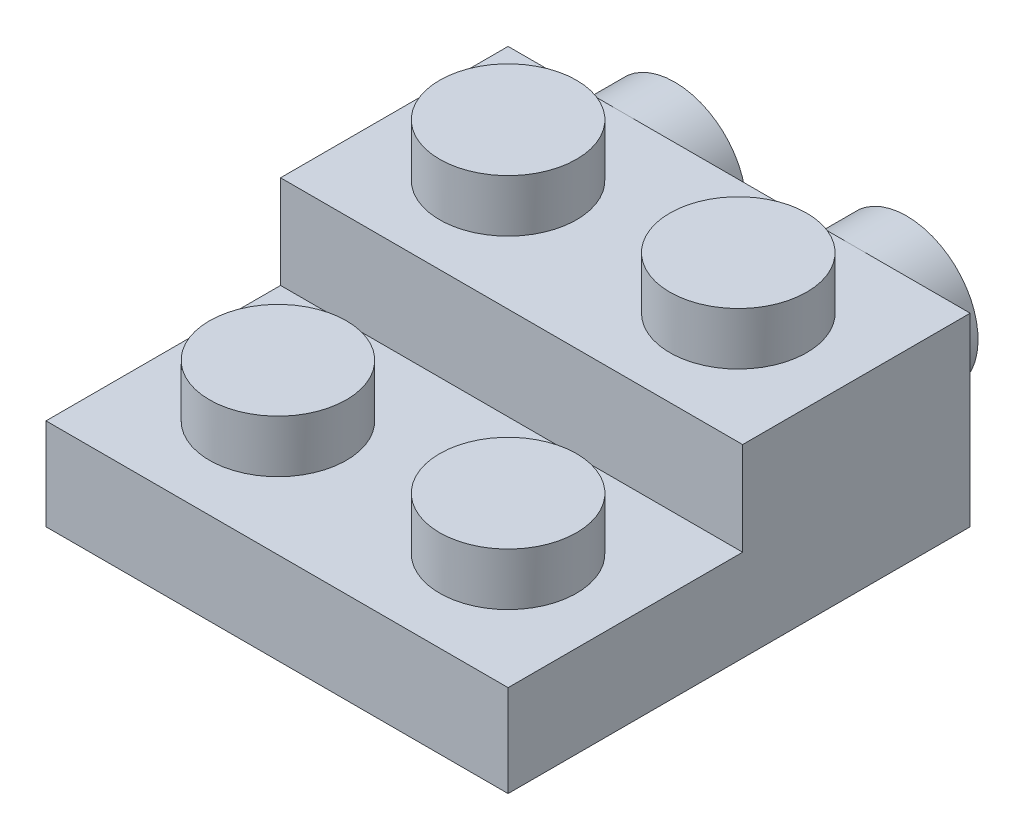
SolidWorks part; units mm, degrees
ref_plane "Front Plane" through (0, 0, 0) normal (0, 0, 1) x (1, 0, 0)
ref_plane "Top Plane" through (0, 0, 0) normal (0, 1, 0) x (1, 0, 0)
ref_plane "Right Plane" through (0, 0, 0) normal (1, 0, 0) x (0, 0, -1)
sketch "Sketch2" plane through (0, 0, 0) normal (1, 0, 0) x (0, 0, -1)
  line L0 (0, 0) -> (0, 6.35)
  line L1 (0, 6.35) -> (-7.81, 6.35)
  line L2 (-7.81, 6.35) -> (-7.81, 3.15)
  line L3 (-7.81, 3.15) -> (-15.86, 3.15)
  line L4 (-15.86, 3.15) -> (-15.86, 0)
  line L5 (-15.86, 0) -> (0, 0)
  dimension "D1" = 6.35
  dimension "D2" = 7.81
  dimension "D3" = 15.86
  dimension "D4" = 3.15
extrude "Boss-Extrude1" add sketch "Sketch2" along normal blind 15.86
sketch "Sketch3" plane through (0, 6.35, 0) normal (0, 1, 0) x (1, 0, 0)
  line L0 (15.86, 0) -> (0, 0) construction
  line L1 (0, 0) -> (0, -7.81) construction
  line L2 (15.86, 0) -> (15.86, -7.81) construction
  circle A0 centre (3.98, -3.98) radius 2.35
  circle A1 centre (11.88, -3.98) radius 2.35
  dimension "D1" = 4.7
  dimension "D2" = 4.7
  dimension "D3" = 3.98
  dimension "D4" = 3.98
  dimension "D5" = 3.98
  dimension "D6" = 3.98
extrude "Boss-Extrude2" add sketch "Sketch3" along normal blind 1.8
sketch "Sketch4" plane through (0, 3.15, 0) normal (0, 1, 0) x (1, 0, 0)
  line L0 (15.86, -15.86) -> (0, -15.86) construction
  line L1 (15.86, -7.81) -> (15.86, -15.86) construction
  line L2 (0, -7.81) -> (0, -15.86) construction
  circle A0 centre (3.98, -11.88) radius 2.35
  circle A1 centre (11.88, -11.88) radius 2.35
  dimension "D1" = 4.7
  dimension "D2" = 4.7
  dimension "D3" = 3.98
  dimension "D4" = 3.98
  dimension "D5" = 3.98
  dimension "D6" = 3.98
extrude "Boss-Extrude3" add sketch "Sketch4" along normal blind 1.8
shell "Shell1" thickness 1.4
sketch "Sketch5" plane through (0, 0, 0) normal (0, 0, -1) x (-1, 0, 0)
  line L0 (-15.86, 0) -> (0, 0) construction
  line L1 (-15.86, 0) -> (-15.86, 6.35) construction
  circle A0 centre (-11.88, 3.9) radius 2.45
  circle A1 centre (-11.88, 3.9) radius 1.45
  circle A2 centre (-3.92, 3.9) radius 1.45
  circle A3 centre (-3.92, 3.9) radius 2.45
  dimension "D3" = 4.9
  dimension "D4" = 2.9
  dimension "D6" = 7.96
  dimension "D1" = 3.9
  dimension "D2" = 3.98
  dimension "D5" = 2
extrude "Boss-Extrude4" add sketch "Sketch5" along normal blind 1.8
sketch "Sketch6" plane through (0, 1.75, 0) normal (0, -1, 0) x (1, 0, 0)
  line L1 (15.86, 15.86) -> (0, 15.86) construction
  line L2 (15.86, 15.86) -> (15.86, 0) construction
  circle A0 centre (7.93, 7.93) radius 3.05
  circle A1 centre (7.93, 7.93) radius 2.395
  dimension "D3" = 6.1
  dimension "D4" = 4.79
  dimension "D1" = 7.93
  dimension "D2" = 7.93
extrude "Boss-Extrude5" add sketch "Sketch6" along normal offset from surface (1.55 mm away) 0.2 up to face at (7.93, 0, 7.93)
